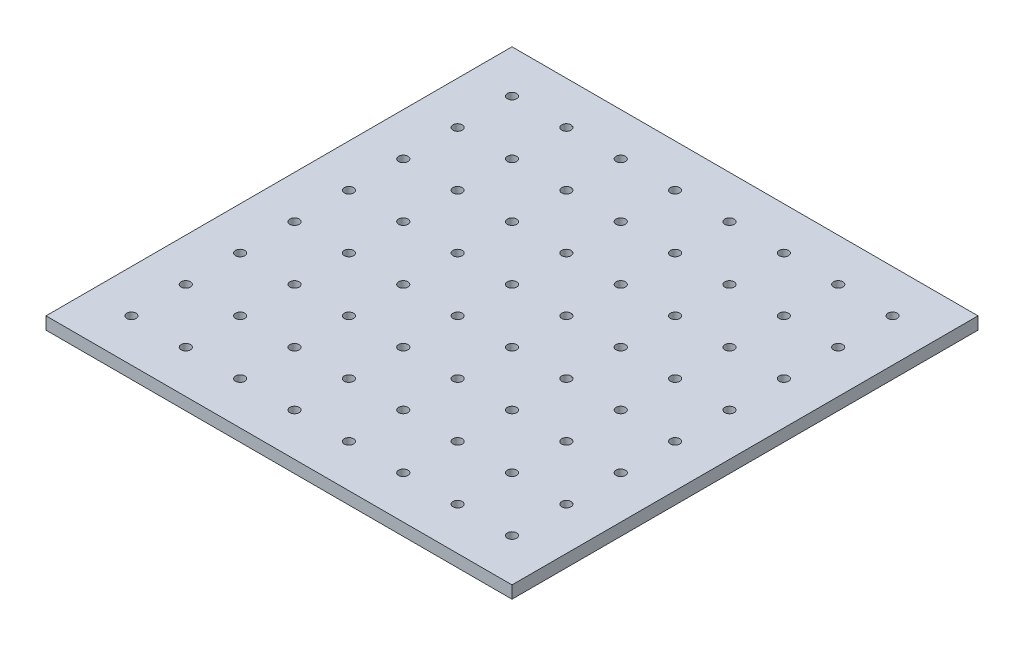
SolidWorks part; units mm, degrees
material "Oak"
ref_plane "Front Plane" through (0, 0, 0) normal (0, 0, 1) x (1, 0, 0)
ref_plane "Top Plane" through (0, 0, 0) normal (0, 1, 0) x (1, 0, 0)
ref_plane "Right Plane" through (0, 0, 0) normal (1, 0, 0) x (0, 0, -1)
sketch "Sketch1" plane through (0, 0, 0) normal (0, 1, 0) x (1, 0, 0)
  line L0 (-61.25, -61.25) -> (-43.75, -61.25) construction
  line L5 (75, 75) -> (-75, 75)
  line L6 (75, 75) -> (75, -75)
  line L7 (75, -75) -> (-75, -75)
  line L8 (-75, 75) -> (-75, -75)
  line L9 (75, 75) -> (-75, -75) construction
  line L10 (75, -75) -> (-75, 75) construction
  line L11 (-61.25, -61.25) -> (-61.25, -43.75) construction
  circle A0 centre (-61.25, -61.25) radius 1.5
  circle A1 centre (-43.75, -61.25) radius 1.5
  circle A2 centre (-26.25, -61.25) radius 1.5
  circle A3 centre (-8.75, -61.25) radius 1.5
  circle A4 centre (8.75, -61.25) radius 1.5
  circle A5 centre (26.25, -61.25) radius 1.5
  circle A6 centre (43.75, -61.25) radius 1.5
  circle A7 centre (61.25, -61.25) radius 1.5
  circle A8 centre (-43.75, -43.75) radius 1.5
  circle A9 centre (-26.25, -43.75) radius 1.5
  circle A10 centre (-8.75, -43.75) radius 1.5
  circle A11 centre (8.75, -43.75) radius 1.5
  circle A12 centre (26.25, -43.75) radius 1.5
  circle A13 centre (43.75, -43.75) radius 1.5
  circle A14 centre (61.25, -43.75) radius 1.5
  circle A15 centre (-43.75, -26.25) radius 1.5
  circle A16 centre (-26.25, -26.25) radius 1.5
  circle A17 centre (-8.75, -26.25) radius 1.5
  circle A18 centre (8.75, -26.25) radius 1.5
  circle A19 centre (26.25, -26.25) radius 1.5
  circle A20 centre (43.75, -26.25) radius 1.5
  circle A21 centre (61.25, -26.25) radius 1.5
  circle A22 centre (-43.75, -8.75) radius 1.5
  circle A23 centre (-26.25, -8.75) radius 1.5
  circle A24 centre (-8.75, -8.75) radius 1.5
  circle A25 centre (8.75, -8.75) radius 1.5
  circle A26 centre (26.25, -8.75) radius 1.5
  circle A27 centre (43.75, -8.75) radius 1.5
  circle A28 centre (61.25, -8.75) radius 1.5
  circle A29 centre (-43.75, 8.75) radius 1.5
  circle A30 centre (-26.25, 8.75) radius 1.5
  circle A31 centre (-8.75, 8.75) radius 1.5
  circle A32 centre (8.75, 8.75) radius 1.5
  circle A33 centre (26.25, 8.75) radius 1.5
  circle A34 centre (43.75, 8.75) radius 1.5
  circle A35 centre (61.25, 8.75) radius 1.5
  circle A36 centre (-43.75, 26.25) radius 1.5
  circle A37 centre (-26.25, 26.25) radius 1.5
  circle A38 centre (-8.75, 26.25) radius 1.5
  circle A39 centre (8.75, 26.25) radius 1.5
  circle A40 centre (26.25, 26.25) radius 1.5
  circle A41 centre (43.75, 26.25) radius 1.5
  circle A42 centre (61.25, 26.25) radius 1.5
  circle A43 centre (-43.75, 43.75) radius 1.5
  circle A44 centre (-26.25, 43.75) radius 1.5
  circle A45 centre (-8.75, 43.75) radius 1.5
  circle A46 centre (8.75, 43.75) radius 1.5
  circle A47 centre (26.25, 43.75) radius 1.5
  circle A48 centre (43.75, 43.75) radius 1.5
  circle A49 centre (61.25, 43.75) radius 1.5
  circle A50 centre (-43.75, 61.25) radius 1.5
  circle A51 centre (-26.25, 61.25) radius 1.5
  circle A52 centre (-8.75, 61.25) radius 1.5
  circle A53 centre (8.75, 61.25) radius 1.5
  circle A54 centre (26.25, 61.25) radius 1.5
  circle A55 centre (43.75, 61.25) radius 1.5
  circle A56 centre (61.25, 61.25) radius 1.5
  circle A57 centre (-61.25, -43.75) radius 1.5
  circle A58 centre (-61.25, -26.25) radius 1.5
  circle A59 centre (-61.25, -8.75) radius 1.5
  circle A60 centre (-61.25, 8.75) radius 1.5
  circle A61 centre (-61.25, 26.25) radius 1.5
  circle A62 centre (-61.25, 43.75) radius 1.5
  circle A63 centre (-61.25, 61.25) radius 1.5
  point P0 (0, 0)
  dimension "D1" = 3
  dimension "D4" = 17.5
  dimension "D5" = 17.5
  dimension "D6" = 150
  dimension "D7" = 150
  dimension "D8" = 8.75
  dimension "D9" = 8.75
  dimension "D2" = 8
  dimension "D3" = 8
extrude "Boss-Extrude1" add sketch "Sketch1" along normal blind 4
equation "\"dist\"=1.75"
equation "\"D5@Sketch1\"=\"dist\""
equation "\"D4@Sketch1\"=\"dist\""
equation "\"D8@Sketch1\"=\"dist\"/2"
equation "\"D9@Sketch1\"=\"D8@Sketch1\""
